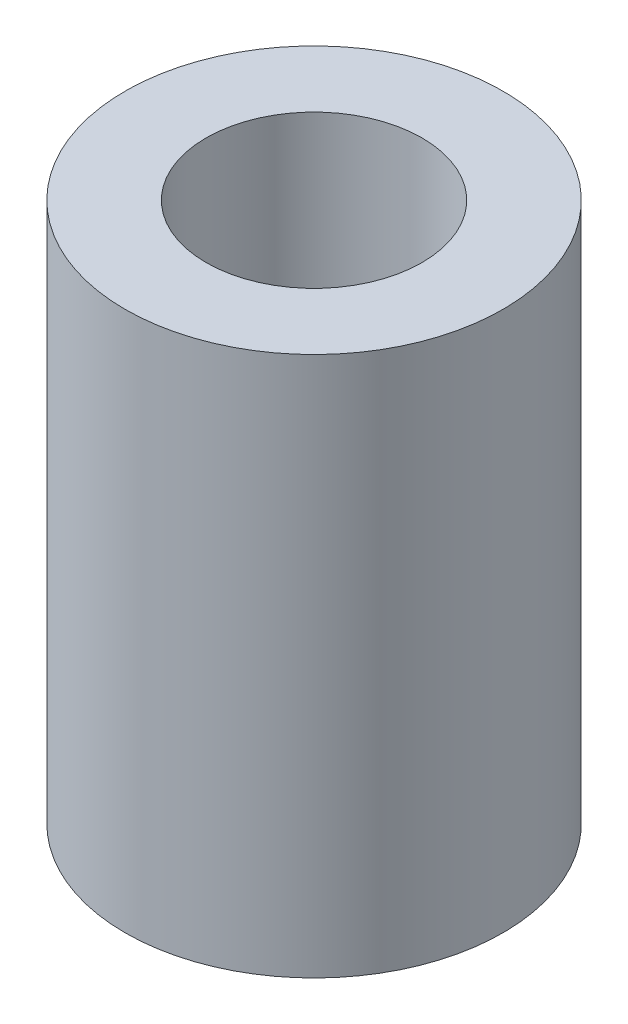
SolidWorks part; units mm, degrees
material "合金钢"
ref_plane "前视基准面" through (0, 0, 0) normal (0, 0, 1) x (1, 0, 0)
ref_plane "上视基准面" through (0, 0, 0) normal (0, 1, 0) x (1, 0, 0)
ref_plane "右视基准面" through (0, 0, 0) normal (1, 0, 0) x (0, 0, -1)
sketch "草图1" plane through (0, 0, 0) normal (0, 1, 0) x (1, 0, 0)
  circle A0 centre (0, 0) radius 10.5
  circle A1 centre (0, 0) radius 6
  dimension "D1" = 12
  dimension "D2" = 21
extrude "凸台-拉伸1" add sketch "草图1" along normal blind 30
